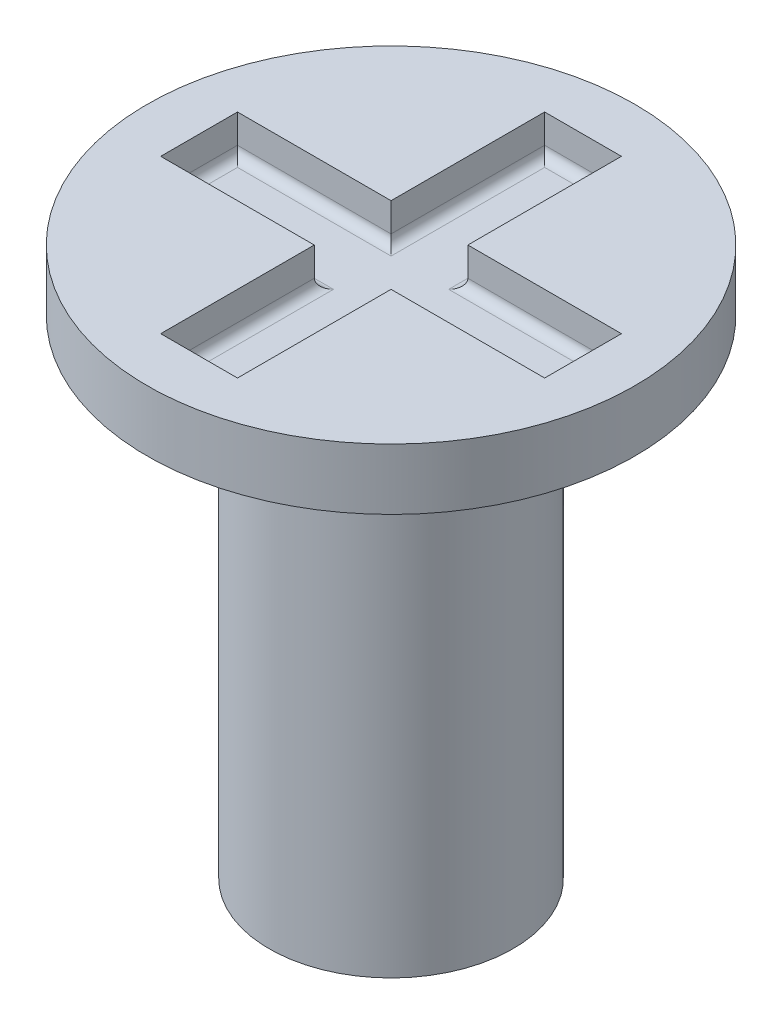
SolidWorks part; units mm, degrees
ref_plane "Front Plane" through (0, 0, 0) normal (0, 0, 1) x (1, 0, 0)
ref_plane "Top Plane" through (0, 0, 0) normal (0, 1, 0) x (1, 0, 0)
ref_plane "Right Plane" through (0, 0, 0) normal (1, 0, 0) x (0, 0, -1)
sketch "Sketch1" plane through (0, 0, 0) normal (0, 0, 1) x (1, 0, 0)
  line L0 (0, 0) -> (0, -0.7937)
  line L1 (0, -0.7937) -> (1.5875, -0.7937)
  line L2 (1.5875, -0.7937) -> (1.5875, -7.1437)
  line L3 (1.5875, -7.1437) -> (3.175, -7.1437)
  line L4 (3.175, -7.1437) -> (3.175, 4.7806) construction
  line L5 (0, 0) -> (3.175, 0)
  line L6 (3.175, -7.1437) -> (3.175, 0)
  dimension "D1" = 1.5875
  dimension "D2" = 6.35
  dimension "D3" = 3.175
  dimension "D4" = 0.7937
revolve "Revolve1" add sketch "Sketch1" angle 360 about L4
sketch "Sketch2" plane through (0, 0, 0) normal (0, 1, 0) x (1, 0, 0)
  line L0 (0.675, 0) -> (5.675, 0)
  line L5 (3.175, 2.5) -> (3.175, -2.5)
  circle A0 centre (3.175, 0) radius 3.175 construction
  point P0 (3.175, 3.175)
  point P1 (0, 0)
  point P4 (3.175, 0)
  point P11 (3.175, 0)
  point P12 (3.175, 0)
  point P13 (0, 0)
  point P14 (0, 0)
  dimension "D1" = 5
  dimension "D2" = 5
extrude "Cut-Extrude-Thin1" cut sketch "Sketch2" against normal blind 0.5 thin thin type mid plane wall 1
fillet "Fillet2" radius 0.125 12 edges at (2.675, -0.5, -1.5) (3.175, -0.5, -2.5) (3.675, -0.5, -1.5) (4.675, -0.5, -0.5) (5.675, -0.5, 0) (4.675, -0.5, 0.5) (3.675, -0.5, 1.5) (3.175, -0.5, 2.5) (2.675, -0.5, 1.5) (1.675, -0.5, 0.5) (0.675, -0.5, 0) (1.675, -0.5, -0.5)
